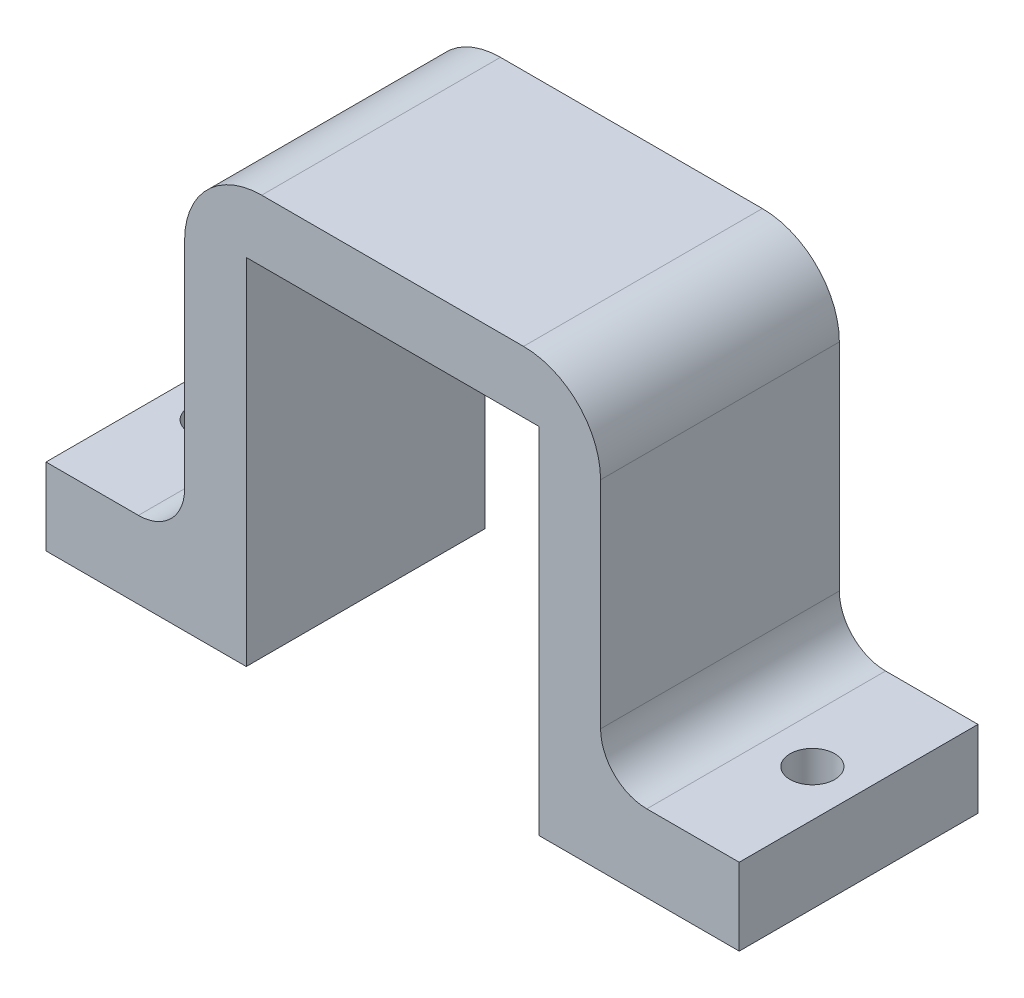
SolidWorks part; units mm, degrees
ref_plane "Front Plane" through (0, 0, 0) normal (0, 0, 1) x (1, 0, 0)
ref_plane "Top Plane" through (0, 0, 0) normal (0, 1, 0) x (1, 0, 0)
ref_plane "Right Plane" through (0, 0, 0) normal (1, 0, 0) x (0, 0, -1)
sketch "Sketch1" plane through (0, 0, 0) normal (0, 0, 1) x (1, 0, 0)
  line L0 (0, 3) -> (0, 17)
  line L1 (5, 22) -> (22, 22)
  line L2 (27, 17) -> (27, 3)
  line L3 (30, 0) -> (36, 0)
  line L4 (36, 0) -> (36, -4)
  line L5 (36, -4) -> (23, -4)
  line L6 (23, -4) -> (23, 18)
  line L7 (23, 18) -> (4, 18)
  line L8 (4, 18) -> (4, -4)
  line L9 (4, -4) -> (-9, -4)
  line L10 (-9, -4) -> (-9, 0)
  line L11 (-9, 0) -> (-3, 0)
  arc A0 (5, 22) -> (0, 17) centre (5, 17) ccw
  arc A1 (22, 22) -> (27, 17) centre (22, 17) cw
  arc A2 (0, 3) -> (-3, 0) centre (-3, 3) cw
  arc A3 (30, 0) -> (27, 3) centre (30, 3) cw
  point P18 (27, 22)
  point P21 (0, 0)
  dimension "D10" = 5
  dimension "D11" = 3
  dimension "D1" = 19
  dimension "D2" = 4
  dimension "D3" = 4
  dimension "D4" = 4
  dimension "D5" = 4
  dimension "D6" = 4
  dimension "D7" = 22
  dimension "D8" = 13
  dimension "D9" = 13
extrude "Boss-Extrude1" add sketch "Sketch1" along normal blind 23
ref_plane "Plane1" through (13.5, 0, 0) normal (1, 0, 0) x (0, 0, -1)
sketch "Sketch3" plane through (0, 0, 0) normal (0, 1, 0) x (1, 0, 0)
  line L0 (-9, -11.5) -> (36, -11.5) construction
  line L1 (-9, -23) -> (-9, 0) construction
  line L2 (36, -23) -> (36, 0) construction
  line L3 (13.5, -12.1) -> (13.5, 12.1) construction
  line L4 (36, 0) -> (30, 0) construction
  line L6 (36, -23) -> (30, -23) construction
  circle A0 centre (-6, -2.25) radius 1.45
  circle A1 centre (-6, -20.75) radius 1.45
  circle A2 centre (33, -20.75) radius 1.45
  circle A3 centre (33, -2.25) radius 1.45
  point P23 (33, -23)
  dimension "D1" = 2.9
  dimension "D2" = 2.25
  dimension "D3" = 2.25
sketch "Sketch4" plane through (0, 0, 0) normal (-1, 0, 0) x (0, 0, 1)
  line L0 (23, 17) -> (0, 17) construction
  line L1 (4, 17) -> (7.5, 17)
  line L2 (4, 17) -> (4, -4)
  line L3 (4, -4) -> (7.5, -4)
  line L4 (7.5, 17) -> (7.5, -4)
  line L5 (23, -4) -> (0, -4) construction
  line L7 (0, 0) -> (0, -4) construction
  dimension "D1" = 4
  dimension "D2" = 3.5
extrude "Cut-Extrude2" cut sketch "Sketch4" against normal blind 10 and the other way blind 23
sketch "Sketch5" plane through (0, 22, 0) normal (0, 1, 0) x (1, 0, 0)
  line L0 (-9, -7.5) -> (36, -7.5) construction
  line L1 (36, -23) -> (36, 0) construction
  line L3 (-9, 0) -> (36, 0)
  line L4 (-9, 0) -> (-9, -7.5)
  line L5 (-9, -7.5) -> (36, -7.5)
  line L6 (36, 0) -> (36, -7.5)
extrude "Cut-Extrude3" cut sketch "Sketch5" against normal blind 26
sketch "Sketch7" plane through (0, 0, 0) normal (0, 1, 0) x (1, 0, 0)
  line L0 (13.5, -8.525) -> (13.5, 8.525) construction
  line L3 (-3, -23) -> (-9, -23) construction
  line L5 (36, -7.5) -> (30, -7.5) construction
  circle A0 centre (-6, -15.25) radius 1.45
  circle A1 centre (33, -15.25) radius 1.45
  point P14 (-6, -23)
  dimension "D1" = 2.9
  dimension "D2" = 7.75
extrude "Cut-Extrude4" cut sketch "Sketch7" against normal blind 50
sketch "Sketch8" plane through (0, -4, 0) normal (0, -1, 0) x (1, 0, 0)
  line L0 (13.5, -8.525) -> (13.5, 8.525) construction
  line L1 (23, 23) -> (36, 23)
  line L2 (23, 23) -> (23, 7.5)
  line L3 (23, 7.5) -> (36, 7.5)
  line L4 (36, 23) -> (36, 7.5)
  line L5 (4, 7.5) -> (-9, 7.5)
  line L6 (-9, 23) -> (-9, 7.5)
  line L7 (4, 23) -> (-9, 23)
  line L8 (4, 23) -> (4, 7.5)
extrude "Boss-Extrude2" add sketch "Sketch8" along normal blind 1
sketch "Sketch9" plane through (0, -4, 0) normal (0, 1, 0) x (1, 0, 0)
  line L0 (13.5, -8.525) -> (13.5, 8.525) construction
  circle A0 centre (33, -15.25) radius 1.45
  circle A1 centre (-6, -15.25) radius 1.45
extrude "Cut-Extrude5" cut sketch "Sketch9" against normal blind 10
